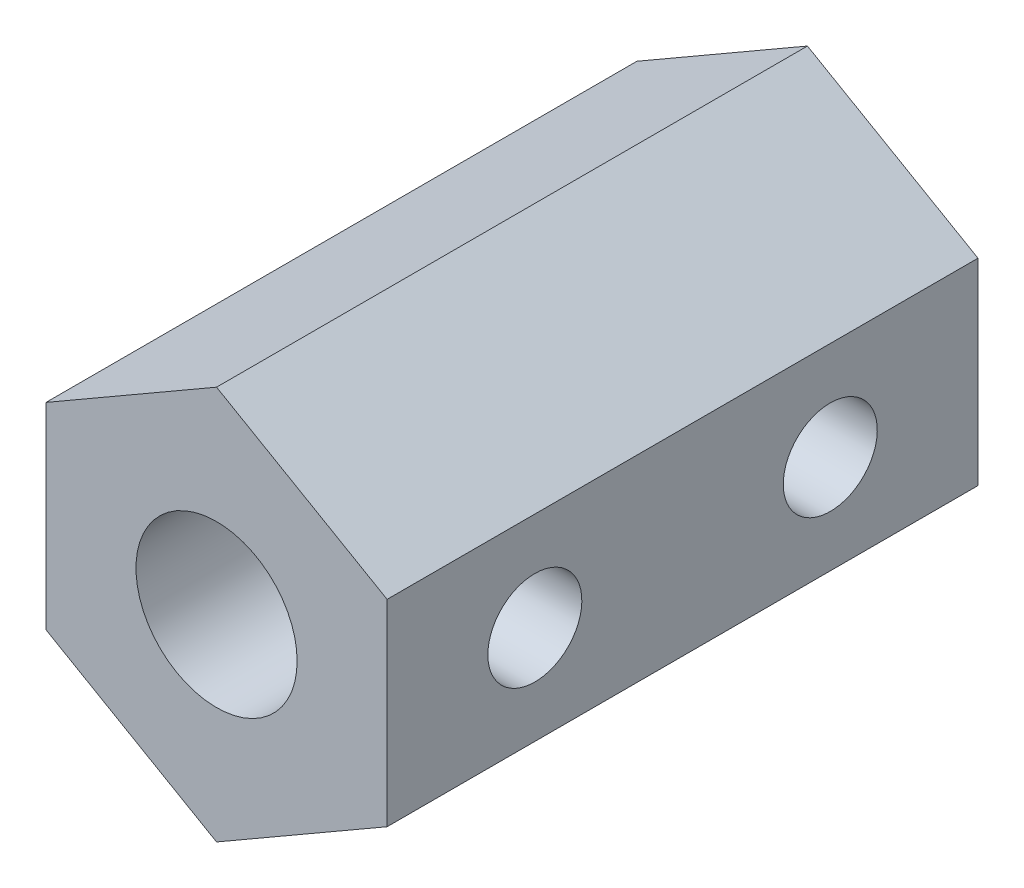
SolidWorks part; units mm, degrees
ref_plane "Plan de face" through (0, 0, 0) normal (0, 0, 1) x (1, 0, 0)
ref_plane "Plan de dessus" through (0, 0, 0) normal (0, 1, 0) x (1, 0, 0)
ref_plane "Plan de droite" through (0, 0, 0) normal (1, 0, 0) x (0, 0, -1)
sketch "Esquisse1" plane through (0, 0, 0) normal (0, 0, 1) x (1, 0, 0)
  line L1 (0, 7.3323) -> (-6.35, 3.6662)
  line L2 (-6.35, 3.6662) -> (-6.35, -3.6662)
  line L3 (-6.35, -3.6662) -> (0, -7.3323)
  line L4 (0, -7.3323) -> (6.35, -3.6662)
  line L5 (6.35, -3.6662) -> (6.35, 3.6662)
  line L6 (6.35, 3.6662) -> (0, 7.3323)
  circle A0 centre (0, 0) radius 6.35 construction
  circle A1 centre (0, 0) radius 3
  dimension "D2" = 6
  dimension "D1" = 12.7
extrude "Boss.-Extru.1" add sketch "Esquisse1" along normal blind 22
sketch "Esquisse3" plane through (6.35, 0, 0) normal (1, 0, 0) x (0, 0, -1)
  line L0 (-22, -3.6662) -> (-22, 3.6662) construction
  circle A0 centre (-5.5, 0) radius 1.75
  circle A1 centre (-16.5, 0) radius 1.75
  dimension "D1" = 3.5
  dimension "D4" = 3.5
  dimension "D2" = 5.5
  dimension "D3" = 5.5
extrude "Enlèv. mat.-Extru.1" cut sketch "Esquisse3" against normal blind 4.5
